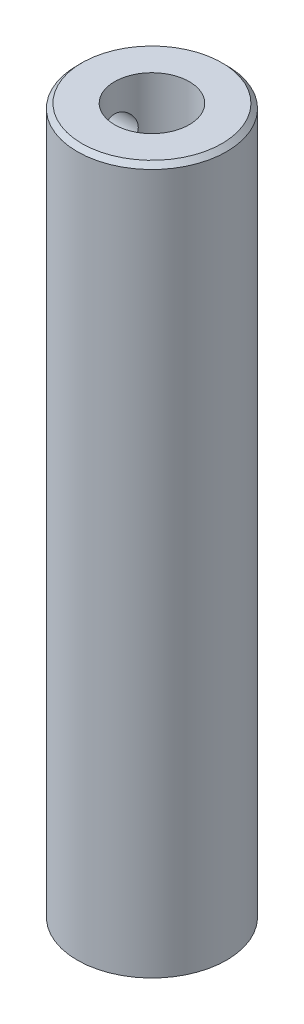
SolidWorks part; units mm, degrees
ref_plane "정면" through (0, 0, 0) normal (0, 0, 1) x (1, 0, 0)
ref_plane "윗면" through (0, 0, 0) normal (0, 1, 0) x (1, 0, 0)
ref_plane "우측면" through (0, 0, 0) normal (1, 0, 0) x (0, 0, -1)
sketch "스케치1" plane through (0, 0, 0) normal (0, 1, 0) x (1, 0, 0)
  circle A0 centre (0, 0) radius 8
  dimension "D1" = 16
extrude "보스-돌출1" add sketch "스케치1" against normal blind 75.5
chamfer "모따기1" distance 0.5 angle 45 1 edges at (0, 0, 8)
sketch "스케치3" plane through (0, 0, 0) normal (0, 1, 0) x (1, 0, 0)
  circle A0 centre (0, 0) radius 4
extrude "컷-돌출1" cut sketch "스케치3" against normal blind 23
sketch "스케치4" plane through (0, 0, 0) normal (1, 0, 0) x (0, 0, -1)
  line L0 (7.5, 0) -> (-7.5, 0) construction
  circle A0 centre (0, -5) radius 2
  dimension "D1" = 5
extrude "컷-돌출2" cut sketch "스케치4" against normal blind 23
